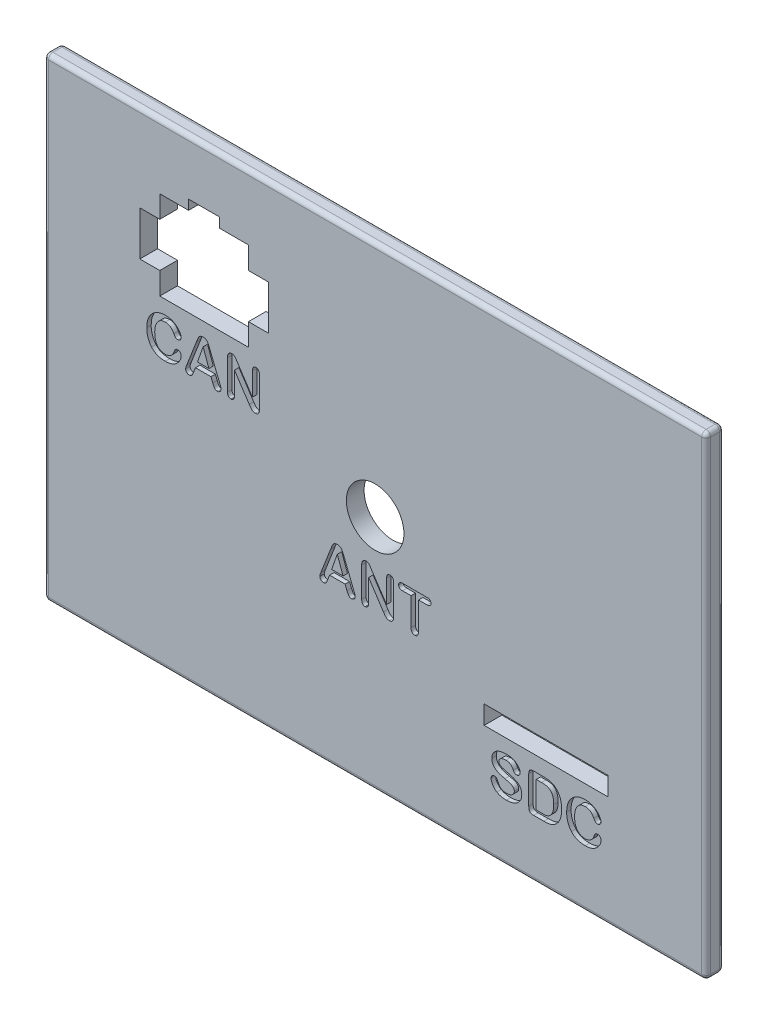
SolidWorks part; units mm, degrees
ref_plane "Front Plane" through (0, 0, 0) normal (0, 0, 1) x (1, 0, 0)
ref_plane "Top Plane" through (0, 0, 0) normal (0, 1, 0) x (1, 0, 0)
ref_plane "Right Plane" through (0, 0, 0) normal (1, 0, 0) x (0, 0, -1)
sketch "Sketch1" plane through (0, 0, 0) normal (0, 0, 1) x (1, 0, 0)
  line L1 (-37.35, -26.75) -> (37.35, -26.75)
  line L2 (-37.35, -26.75) -> (-37.35, 26.75)
  line L3 (-37.35, 26.75) -> (37.35, 26.75)
  line L4 (37.35, -26.75) -> (37.35, 26.75)
  line L5 (-37.35, -26.75) -> (37.35, 26.75) construction
  line L6 (-37.35, 26.75) -> (37.35, -26.75) construction
  point P0 (0, 0)
  dimension "D1" = 74.7
  dimension "D2" = 53.5
extrude "Boss-Extrude1" add sketch "Sketch1" along normal blind 2
sketch "Sketch5" plane through (0, 0, 2) normal (0, 0, 1) x (1, 0, 0)
  line L0 (-37.35, 26.75) -> (-37.35, -26.75) construction
  line L1 (-14.3, 9.45) -> (-24.3, 9.45)
  line L2 (-14.3, 9.45) -> (-14.3, 19.45)
  line L3 (-14.3, 19.45) -> (-24.3, 19.45)
  line L4 (-24.3, 9.45) -> (-24.3, 19.45)
  line L5 (-14.3, 9.45) -> (-24.3, 19.45) construction
  line L6 (-14.3, 19.45) -> (-24.3, 9.45) construction
  line L7 (-12.05, 11.95) -> (-26.55, 11.95)
  line L8 (-12.05, 11.95) -> (-12.05, 16.95)
  line L9 (-12.05, 16.95) -> (-26.55, 16.95)
  line L10 (-26.55, 11.95) -> (-26.55, 16.95)
  line L11 (-12.05, 11.95) -> (-26.55, 16.95) construction
  line L12 (-12.05, 16.95) -> (-26.55, 11.95) construction
  line L13 (-21.05, 20.55) -> (-17.55, 20.55)
  line L14 (-21.05, 20.55) -> (-21.05, 14.45)
  line L15 (-21.05, 14.45) -> (-17.55, 14.45)
  line L16 (-17.55, 20.55) -> (-17.55, 14.45)
  line L17 (12.3, -12.1) -> (26.3, -12.1)
  line L18 (12.3, -12.1) -> (12.3, -14.2)
  line L19 (12.3, -14.2) -> (26.3, -14.2)
  line L20 (26.3, -12.1) -> (26.3, -14.2)
  line L21 (-35.35, 26.75) -> (35.35, 26.75) construction
  line L22 (-35.35, 26.75) -> (-35.35, -24.75) construction
  line L23 (-35.35, -24.75) -> (35.35, -24.75) construction
  line L24 (35.35, 26.75) -> (35.35, -24.75) construction
  line L25 (4, 3.25) -> (4, -20.75) construction
  line L26 (37.35, -26.75) -> (37.35, 26.75) construction
  line L27 (-37.35, -26.75) -> (37.35, -26.75) construction
  line L28 (37.35, 26.75) -> (-37.35, 26.75) construction
  line L29 (10.3, -14.2) -> (28.3, -14.2) construction
  line L34 (10.3, -14.2) -> (10.3, -15.9) construction
  line L35 (10.3, -15.9) -> (28.3, -15.9) construction
  line L36 (28.3, -14.2) -> (28.3, -15.9) construction
  line L37 (4, -20.75) -> (0, -20.75) construction
  line L38 (0, -20.75) -> (0, 3.25) construction
  line L39 (0, 3.25) -> (4, 3.25) construction
  line L40 (-3.25, 0) -> (-3.25, 14.45) construction
  line L41 (-35.35, 14.45) -> (-26.55, 14.45) construction
  line L42 (-3.25, 14.45) -> (-12.05, 14.45) construction
  line L43 (0, -3.25) -> (35.35, -3.25) construction
  line L44 (26.3, -13.15) -> (35.35, -13.15) construction
  line L45 (0, 3.25) -> (-35.35, 3.25) construction
  line L46 (12.3, -13.15) -> (3.25, -13.15) construction
  line L47 (3.25, -13.15) -> (3.25, 0) construction
  line L48 (-19.3, 9.45) -> (-19.3, 3.25) construction
  line L49 (-19.3, 20.55) -> (-19.3, 26.75) construction
  line L50 (19.3, -15.9) -> (19.3, -24.75) construction
  line L51 (19.3, -12.1) -> (19.3, -3.25) construction
  circle A1 centre (0, 0) radius 3.25
  point P0 (-19.3, 14.45)
  point P6 (-19.3, 14.45)
  point P26 (19.3, -14.2)
  dimension "D19" = 6.5
  dimension "D1" = 5
  dimension "D2" = 10
  dimension "D3" = 3.5
  dimension "D4" = 1.1
  dimension "D5" = 14.5
  dimension "D6" = 10
  dimension "D8" = 2.1
  dimension "D9" = 14
  dimension "D10" = 2
  dimension "D12" = 2
  dimension "D13" = 2
  dimension "D15" = 18
  dimension "D16" = 1.7
  dimension "D17" = 4
  dimension "D18" = 24
extrude "Cut-Extrude1" cut sketch "Sketch5" against normal through all contours A1 | L20 L17 L18 L19 | L10 L7 L4 L9 | L14 L3 L4 L9 | L16 L3 L14 L9
fillet "Fillet1" radius 0.5 12 edges at (0, -26.75, 2) (0, -26.75, 0) (-37.35, 0, 2) (-37.35, -26.75, 1) (-37.35, 0, 0) (0, 26.75, 2) (-37.35, 26.75, 1) (0, 26.75, 0) (37.35, -26.75, 1) (37.35, 0, 2) (37.35, 26.75, 1) (37.35, 0, 0)
sketch "Sketch6" plane through (0, 0, 2) normal (0, 0, 1) x (1, 0, 0)
  line L0 (-7.9934, 0) -> (7.9934, 0) construction
  line L1 (-26.55, 14.45) -> (-12.05, 14.45) construction
  line L2 (-26.55, 14.45) -> (-26.55, 3.45) construction
  line L3 (-26.55, 3.45) -> (-12.05, 3.45) construction
  line L4 (-12.05, 14.45) -> (-12.05, 3.45) construction
  line L5 (-7.9934, 0) -> (-7.9934, -9.25) construction
  line L6 (-7.9934, -9.25) -> (7.9934, -9.25) construction
  line L7 (7.9934, 0) -> (7.9934, -9.25) construction
  line L8 (12.3, -20.2) -> (26.3, -20.2) construction
  line L9 (12.3, -20.2) -> (12.3, -14.2) construction
  line L10 (12.3, -14.2) -> (26.3, -14.2) construction
  line L11 (26.3, -20.2) -> (26.3, -14.2) construction
  line L12 (-12.05, 11.95) -> (-12.05, 16.95) construction
  line L13 (-26.55, 11.95) -> (-26.55, 16.95) construction
  line L14 (-14.3, 9.45) -> (-24.3, 9.45) construction
  line L15 (-7.9934, -3.25) -> (7.9934, -3.25) construction
  circle A0 centre (0, 0) radius 3.25 construction
  text T0 "CAN" font "Arial Rounded MT Bold" height 4.5
  text T1 "SDC" font "Arial Rounded MT Bold" height 4.5
  text T2 "ANT" font "Arial Rounded MT Bold" height 4.5
  point P12 (3.25, 0)
  point P13 (-3.25, 0)
  point P17 (0, 0)
  point P20 (10.4732, 0)
  point P21 (0, 0)
  point P24 (-7.9934, 0)
  dimension "D1" = 6
  dimension "D2" = 6
  dimension "D3" = 6
  dimension "D4" = 15.9869
extrude "Cut-Extrude2" cut sketch "Sketch6" against normal blind 0.5
